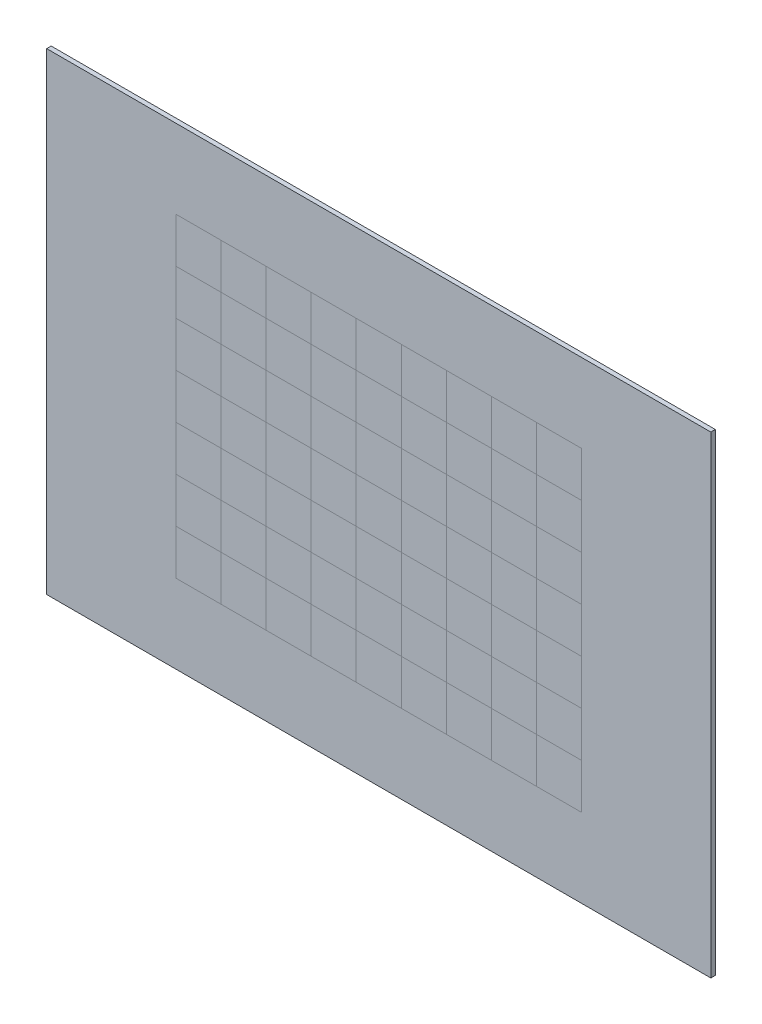
SolidWorks part; units mm, degrees
ref_plane "Front Plane" through (0, 0, 0) normal (0, 0, 1) x (1, 0, 0)
ref_plane "Top Plane" through (0, 0, 0) normal (0, 1, 0) x (1, 0, 0)
ref_plane "Right Plane" through (0, 0, 0) normal (1, 0, 0) x (0, 0, -1)
sketch "Sketch1" plane through (0, 0, 0) normal (0, 0, 1) x (1, 0, 0)
  line L1 (0, 0) -> (100, 0)
  line L2 (0, 0) -> (0, -100)
  line L3 (0, -100) -> (100, -100)
  line L4 (100, 0) -> (100, -100)
  dimension "D1" = 100
extrude "Boss-Extrude1" add sketch "Sketch1" along normal blind 10
pattern_linear "LPattern1" count 9 spacing 100 along (1, 0, 0) count 7 spacing 100 along (0, -1, 0) of "Boss-Extrude1"
sketch "Sketch2" plane through (0, 0, 0) normal (0, 0, 1) x (1, 0, 0)
  line L0 (-287.5, 175) -> (1187.5, -875) construction
  line L1 (0, 0) -> (900, 0)
  line L2 (0, 0) -> (0, -700)
  line L3 (0, -700) -> (900, -700)
  line L4 (900, 0) -> (900, -700)
  line L5 (-287.5, 175) -> (1187.5, 175)
  line L6 (-287.5, 175) -> (-287.5, -875)
  line L7 (-287.5, -875) -> (1187.5, -875)
  line L8 (1187.5, 175) -> (1187.5, -875)
  line L9 (500, -300) -> (400, -400) construction
  point P14 (450, -350)
  point P15 (0, 0)
  dimension "D1" = 1475
  dimension "D2" = 1050
extrude "Boss-Extrude2" add sketch "Sketch2" along normal blind 10 separate body
